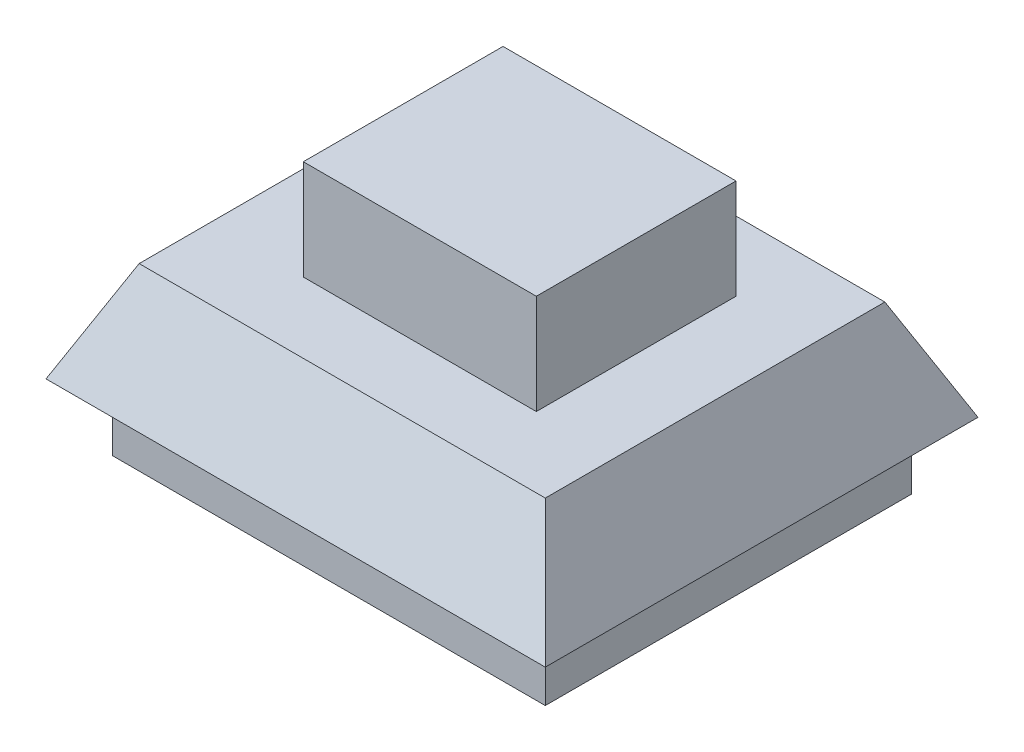
SolidWorks part; units mm, degrees
ref_plane "Front Plane" through (0, 0, 0) normal (0, 0, 1) x (1, 0, 0)
ref_plane "Top Plane" through (0, 0, 0) normal (0, 1, 0) x (1, 0, 0)
ref_plane "Right Plane" through (0, 0, 0) normal (1, 0, 0) x (0, 0, -1)
sketch "Sketch1" plane through (0, 0, 0) normal (0, 1, 0) x (1, 0, 0)
  line L1 (-9.4766, 5.5888) -> (5.5234, 5.5888)
  line L2 (-9.4766, 5.5888) -> (-9.4766, -7.4112)
  line L3 (-9.4766, -7.4112) -> (5.5234, -7.4112)
  line L4 (5.5234, 5.5888) -> (5.5234, -7.4112)
  dimension "D1" = 15
  dimension "D2" = 13
extrude "Boss-Extrude1" add sketch "Sketch1" along normal blind 3 draft 25
sketch "Sketch2" plane through (0, 3, 0) normal (0, 1, 0) x (1, 0, 0)
  line L1 (-5.2613, 2.1042) -> (1.7387, 2.1042)
  line L2 (-5.2613, 2.1042) -> (-5.2613, -3.8958)
  line L3 (-5.2613, -3.8958) -> (1.7387, -3.8958)
  line L4 (1.7387, 2.1042) -> (1.7387, -3.8958)
  line L5 (-5.2613, 2.1042) -> (1.7387, -3.8958) construction
  line L6 (-5.2613, -3.8958) -> (1.7387, 2.1042) construction
  point P0 (-1.7613, -0.8958)
  point P5 (-1.9151, -0.9881)
  point P6 (-1.7613, -0.8958)
  dimension "D1" = 7
  dimension "D2" = 6
extrude "Boss-Extrude2" add sketch "Sketch2" along normal blind 3
sketch "Sketch4" plane through (0, 0, 0) normal (0, -1, 0) x (1, 0, 0)
  line L0 (-9.4766, 7.4112) -> (5.5234, 7.4112) construction
  line L1 (5.5234, 7.4112) -> (5.5234, -5.5888) construction
  line L2 (5.5234, 7.4112) -> (5.5234, -5.5888) construction
  line L3 (-9.4766, -5.5888) -> (-9.4766, 7.4112) construction
  line L4 (-8.4766, 6.4112) -> (4.5234, 6.4112)
  line L5 (-8.4766, 6.4112) -> (-8.4766, -4.5888)
  line L6 (-8.4766, -4.5888) -> (4.5234, -4.5888)
  line L7 (4.5234, 6.4112) -> (4.5234, -4.5888)
  line L8 (-8.4766, 6.4112) -> (4.5234, -4.5888) construction
  line L9 (-8.4766, -4.5888) -> (4.5234, 6.4112) construction
  point P4 (-1.9766, 0.9112)
  point P12 (-1.9766, 7.4112)
  point P15 (-9.4766, 0.9112)
  dimension "D1" = 13
  dimension "D2" = 11
  dimension "D3" = 0
  dimension "D4" = 0
extrude "Boss-Extrude3" add sketch "Sketch4" along normal blind 2
